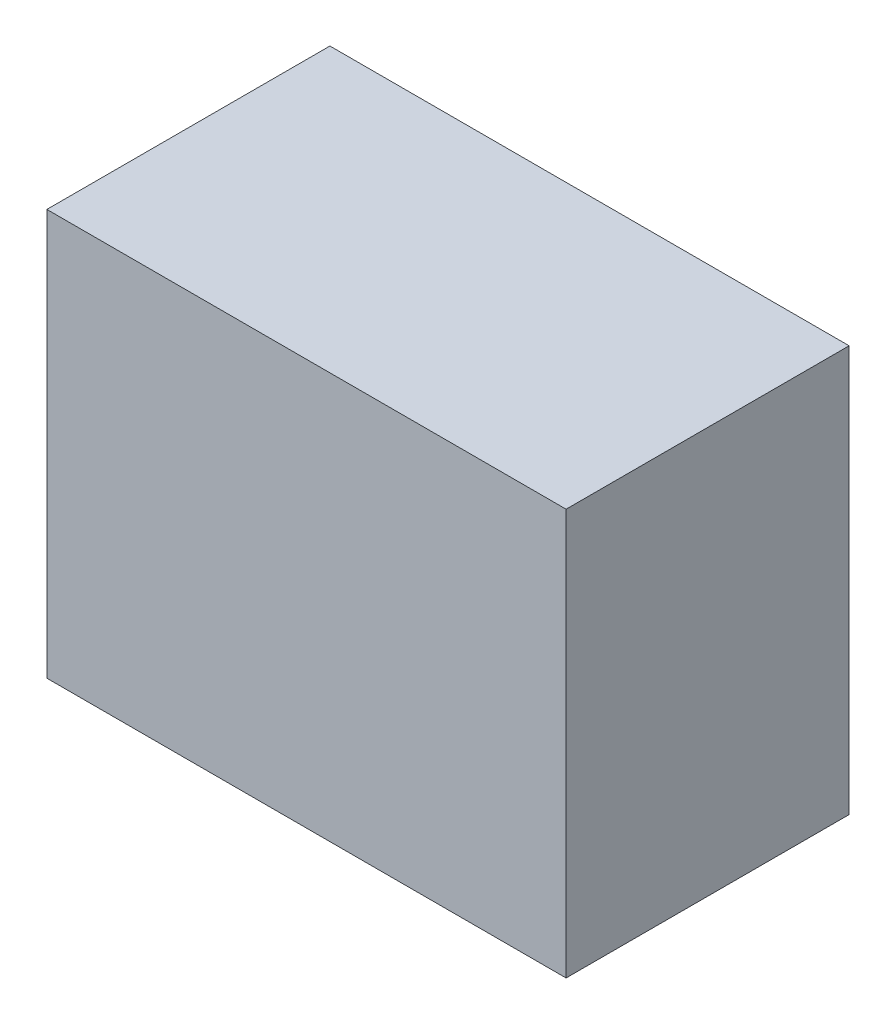
SolidWorks part; units mm, degrees
ref_plane "Front Plane" through (0, 0, 0) normal (0, 0, 1) x (1, 0, 0)
ref_plane "Top Plane" through (0, 0, 0) normal (0, 1, 0) x (1, 0, 0)
ref_plane "Right Plane" through (0, 0, 0) normal (1, 0, 0) x (0, 0, -1)
sketch "Sketch1" plane through (0, 0, 0) normal (0, 0, 1) x (1, 0, 0)
  line L1 (0, 0) -> (26.6, 0)
  line L2 (0, 0) -> (0, 20.8)
  line L3 (0, 20.8) -> (26.6, 20.8)
  line L4 (26.6, 0) -> (26.6, 20.8)
  dimension "D1" = 20.8
  dimension "D2" = 26.6
extrude "Boss-Extrude1" add sketch "Sketch1" along normal blind 14.5
